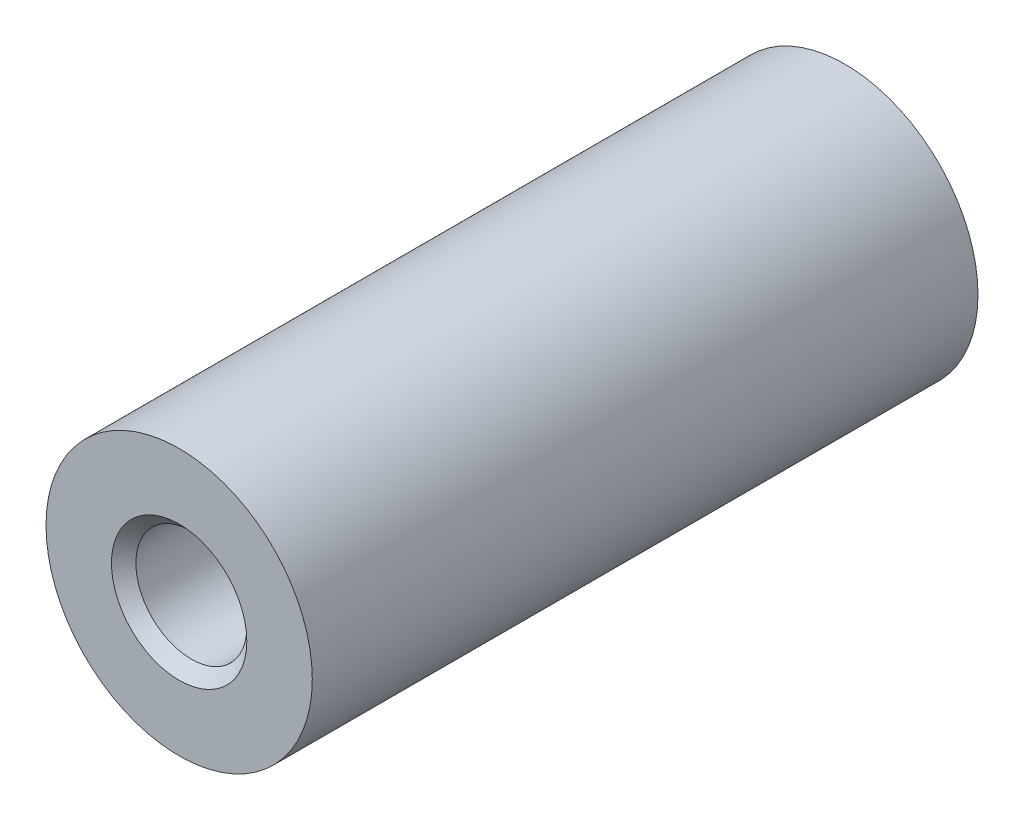
SolidWorks part; units mm, degrees
material "1060 合金"
ref_plane "前视基准面" through (0, 0, 0) normal (0, 0, 1) x (1, 0, 0)
ref_plane "上视基准面" through (0, 0, 0) normal (0, 1, 0) x (1, 0, 0)
ref_plane "右视基准面" through (0, 0, 0) normal (1, 0, 0) x (0, 0, -1)
sketch "草图1" plane through (0, 0, 0) normal (0, 0, 1) x (1, 0, 0)
  circle A0 centre (0, 0) radius 3
  dimension "D1" = 6
extrude "凸台-拉伸1" add sketch "草图1" along normal blind 15
hole_wizard "M3 螺纹孔1" positions "3D草图1" profile "草图2" tap size "M3" standard "GB" end condition through all
sketch3d "3D草图1"
  line L0 (0, 0, 15) -> (0, 0, 0) construction
  point P0 (0, 0, 15)
sketch "草图2" plane through (0, 0, 15) normal (1, 0, 0) x (0, -1, 0)
  line L0 (0, 0) -> (0, 15)
  line L1 (0, 15) -> (1.25, 15)
  line L2 (1.25, 15) -> (1.25, 0.275)
  line L3 (1.25, 0.275) -> (1.525, 0)
  line L5 (1.525, 0) -> (0, 0)
  line L6 (-1.25, 0.275) -> (-1.525, 0) construction
  line L11 (0, -6.35) -> (0, 107.95) construction
  dimension "通孔螺纹孔钻头直径" = 2.5
  dimension "通孔螺纹孔钻头深度" = 15
  dimension "近端锥形沉头孔直径" = 3.05
  dimension "近端锥形沉头孔角度" = 90
cosmetic thread "孔螺蚊线1"
